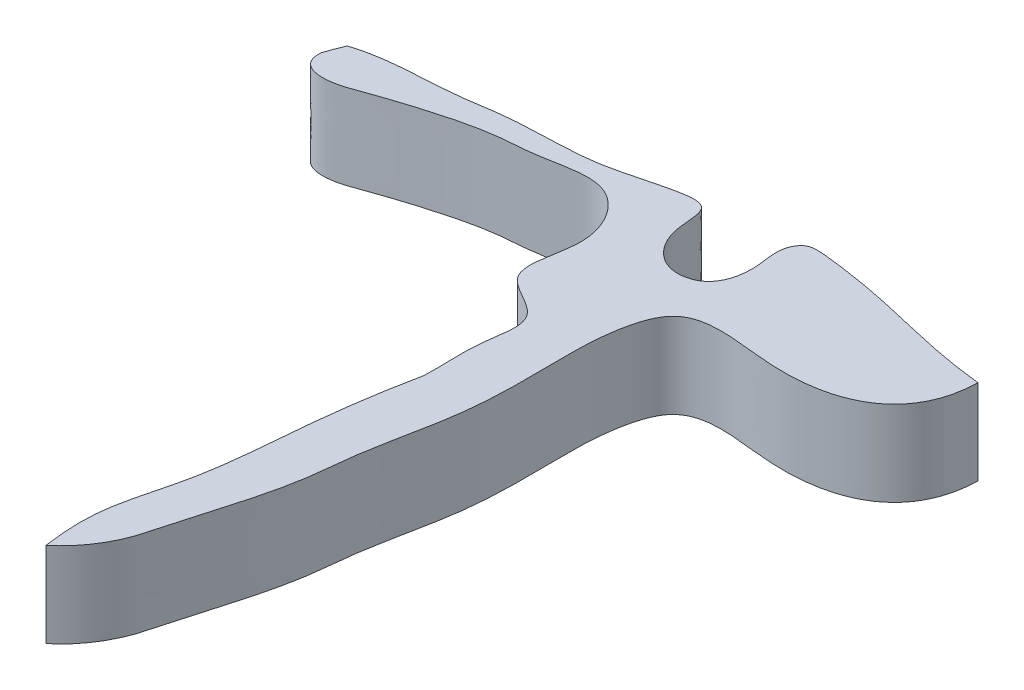
SolidWorks part; units mm, degrees
ref_plane "Front Plane" through (0, 0, 0) normal (0, 0, 1) x (1, 0, 0)
ref_plane "Top Plane" through (0, 0, 0) normal (0, 1, 0) x (1, 0, 0)
ref_plane "Right Plane" through (0, 0, 0) normal (1, 0, 0) x (0, 0, -1)
sketch "Sketch1" plane through (0, 0, 0) normal (0, 1, 0) x (1, 0, 0)
  line L0 (132.9208, 498.8792) -> (664.6039, 498.8792) construction
  spline S0 degree 3 poles (47.4452, 177.9518) (47.0254, 174.6028) (51.7593, 173.3412) (58.5168, 175.9883) (66.5294, 178.5609) (74.6759, 180.5916) (83.6389, 180.9303) (93.9024, 184.3691) (101.5901, 172.2989) (95.3588, 160.0205) (107.8833, 156.8361) (105.1716, 146.4959) (105.9458, 141.0781) (105.7573, 137.4199) knots 0 0 0 0 0.06805 0.126735 0.221277 0.325873 0.379658 0.499724 0.610693 0.730784 0.814837 0.89369 1 1 1 1
  spline S1 degree 3 poles (155.7138, 185.222) (155.4259, 173.1007) (140.4833, 166.9041) (118.937, 172.6125) (115.1926, 160.3303) (115.3483, 149.6177) (115.4446, 134.451) (112.0454, 122.272) (110.8252, 106.92) (107.256, 97.0985) (104.2872, 85.0571) (101.3268, 80.6207) (98.3712, 78.2317) knots 0 0 0 0 0.208505 0.326502 0.372957 0.455667 0.565003 0.69472 0.729434 0.891839 0.917523 1 1 1 1
  spline S2 degree 3 poles (101.3548, 63.7794) (107.1178, 76.7217) (120.4734, 89.8974) (142.3175, 99.8069) (151.7631, 112.7172) (156.6801, 127.2081) (155.0264, 140.7672) (165.9474, 153.3802) (166.4727, 165.3798) (166.4755, 181.7719) (162.7822, 182.2458) (155.7138, 185.222) knots 0 0 0 0 0.265264 0.365208 0.471004 0.575449 0.659468 0.752228 0.920298 0.960402 1 1 1 1
  spline S3 degree 3 poles (155.7138, 185.222) (143.3424, 186.5142) (135.7629, 190.1238) (119.6774, 191.4927) (117.3842, 188.1181) (119.1021, 183.0572) (117.4691, 176.1578) (109.7608, 174.5784) (104.9249, 180.5533) (105.8438, 189.0401) (96.5318, 187.2896) (86.9833, 184.162) (76.6059, 184.9315) (62.0967, 182.3633) (54.5279, 182.9985) (48.6859, 181.0303) knots 0 0 0 0 0.237105 0.256899 0.271012 0.314513 0.364495 0.396714 0.458476 0.498896 0.536122 0.613435 0.730761 0.758905 0.894881 0.894881 0.894881 0.894881
  spline S4 degree 3 poles (84.9542, 23.3748) (72.9575, 20.6745) (71.9674, 25.3606) (66.9703, 32.7264) (63.4633, 41.9395) (58.2122, 48.0409) (50.9968, 58.5561) (50.556, 70.2906) (44.9009, 87.4175) (33.1092, 103.9114) (26.3976, 123.9499) (14.0657, 144.8797) (18.6923, 155.8246) (22.3599, 168.9734) (39.2401, 181.2367) (43.1213, 181.0681) (48.6859, 181.0303) knots 0 0 0 0 0.04448 0.090013 0.138443 0.188153 0.244036 0.300209 0.390948 0.496437 0.613722 0.738952 0.786998 0.806175 0.930725 1 1 1 1
  spline S5 degree 2 poles (24.0375, 145.517) (24.6154, 168.8223) (46.572, 170.2544) knots 0 0 0 1 1 1
  spline S6 degree 3 poles (-2.5807, 150.5978) (25.3813, 187.2619) (71.2737, 199.7007) (119.1491, 205.3389) (188.8296, 188.5694) (163.6488, 122.953) (140.6923, 82.7557) (115.9514, 49.3428) (100.949, 22.7917) (69.9866, 8.4884) (58.9808, 34.5354) (42.6701, 50.0351) (32.6824, 78.02) (22.4132, 112.2265) (-2.5807, 150.5978) (25.3813, 187.2619) (71.2737, 199.7007) knots -0.214288 -0.144168 -0.056107 0 0.077118 0.196257 0.282165 0.391017 0.484824 0.558197 0.611423 0.659102 0.699139 0.739781 0.785712 0.855832 0.943893 1 1.077118 1.196257 1.282165 only from (24.0375, 181.0303) to (24.0375, 181.0303)
  spline S7 degree 2 poles (46.572, 170.2544) (45.9126, 174.769) (48.6859, 181.0303) knots 0.88449 0.88449 0.88449 1 1 1
  spline S8 degree 3 poles (24.0375, 145.517) (24.2622, 143.639) (25.4171, 138.1348) (30.0077, 128.3576) (39.7991, 121.1152) (43.2129, 110.1463) (48.655, 97.0574) (49.9673, 86.7279) (54.646, 75.4111) (57.5935, 57.5488) (72.352, 47.8516) (69.1404, 35.825) (82.724, 21.3135) (91.461, 26.0846) (99.36, 34.146) (106.4591, 48.0552) (101.5336, 62.2605) (98.8404, 74.4776) (96.8682, 87.5544) (101.8022, 102.1432) (102.7904, 119.2975) (104.336, 130.4469) (105.7536, 137.4018) (105.7573, 137.4199) knots 0.084883 0.084883 0.084883 0.084883 0.10777 0.154078 0.187829 0.232552 0.269709 0.335229 0.347597 0.388302 0.400297 0.462464 0.490432 0.503111 0.523547 0.568461 0.596541 0.621395 0.653634 0.683153 0.723781 0.766209 0.766319 0.766319 0.766319 0.766319
extrude "Boss-Extrude1" add sketch "Sketch1" along normal blind 15 contours S8 S1 S3 S7 S0
